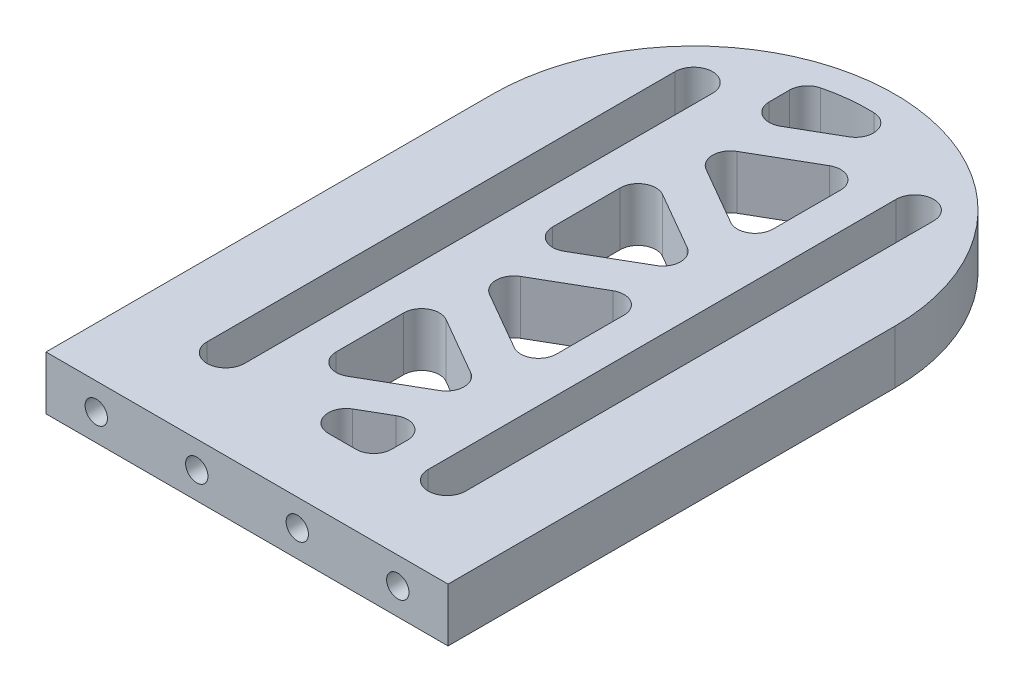
SolidWorks part; units mm, degrees
material "Сплав 2024"
ref_plane "Спереди" through (0, 0, 0) normal (0, 0, 1) x (1, 0, 0)
ref_plane "Сверху" through (0, 0, 0) normal (0, 1, 0) x (1, 0, 0)
ref_plane "Справа" through (0, 0, 0) normal (1, 0, 0) x (0, 0, -1)
sketch "Эскиз1" plane through (0, 0, 0) normal (0, 1, 0) x (1, 0, 0)
  line L2 (-15.9099, 15.9099) -> (15.9099, -15.9099) construction
  line L3 (15.9099, 15.9099) -> (-15.9099, -15.9099) construction
  line L4 (-22.5, 0) -> (-22.5, -50)
  line L5 (-22.5, -50) -> (22.5, -50)
  line L6 (22.5, 0) -> (22.5, -50)
  arc A0 (22.5, 0) -> (-22.5, 0) centre (0, 0) ccw
  dimension "D1" = 45
  dimension "D2" = 50
  dimension "D3" = 45
extrude "Бобышка-Вытянуть1" add sketch "Эскиз1" along normal blind 6
sketch "Эскиз2" plane through (0, 6, 0) normal (0, 1, 0) x (1, 0, 0)
  line L0 (-12.3744, -12.3744) -> (12.3744, 12.3744) construction
  line L1 (-36.6046, 36.6046) -> (36.6046, -36.6046) construction
  line L2 (22.5, -50) -> (22.5, 0) construction
  line L3 (-12.3744, 28.2466) -> (-12.3744, -50.5484) construction
  line L4 (12.3744, 23.4168) -> (12.3744, -56.6851) construction
  line L5 (-12.3744, 12.3744) -> (-12.3744, -40) construction
  line L6 (-10.2744, 12.3744) -> (-10.2744, -40)
  line L7 (-14.4744, 12.3744) -> (-14.4744, -40)
  line L8 (-22.5, -50) -> (22.5, -50) construction
  line L9 (0, 10.4779) -> (0, -10.8682) construction
  line L10 (12.3744, 12.3744) -> (12.3744, -40) construction
  line L11 (10.2744, 12.3744) -> (10.2744, -40)
  line L12 (14.4744, 12.3744) -> (14.4744, -40)
  circle A0 centre (0, 0) radius 6 construction
  circle A1 centre (0, 0) radius 17.5 construction
  arc A2 (-10.2744, 12.3744) -> (-14.4744, 12.3744) centre (-12.3744, 12.3744) ccw
  arc A3 (-14.4744, -40) -> (-10.2744, -40) centre (-12.3744, -40) ccw
  arc A4 (10.2744, 12.3744) -> (14.4744, 12.3744) centre (12.3744, 12.3744) cw
  arc A5 (14.4744, -40) -> (10.2744, -40) centre (12.3744, -40) cw
  point P12 (-12.3744, 12.3744)
  point P13 (12.3744, 12.3744)
  point P18 (-12.3744, -13.8128)
  point P28 (12.3744, -13.8128)
  dimension "D1" = 12
  dimension "D2" = 35
  dimension "D4" = 2.1
  dimension "D3" = 45
  dimension "D5" = 10
hole_wizard "Цековка для  винта с полукруглой головкой M31" [suppressed] positions "Эскиз4" profile "Эскиз5" counterbore size "M3" standard "Ansi Metric"
sketch "Эскиз4" plane through (0, 6, 0) normal (0, 1, 0) x (1, 0, 0)
  line L2 (-36.6046, 36.6046) -> (36.6046, -36.6046) construction
  line L3 (-12.3744, -12.3744) -> (12.3744, 12.3744) construction
  circle A0 centre (0, 0) radius 6 construction
  point P0 (-4.2426, 4.2426)
  point P6 (-4.2426, -4.2426)
  point P10 (4.2426, -4.2426)
  point P12 (4.2426, 4.2426)
sketch "Эскиз5" plane through (-4.2426, 6, -4.2426) normal (1, 0, 0) x (0, 0, 1)
  line L0 (0, 0) -> (0, 6)
  line L1 (0, 6) -> (1.7, 6)
  line L3 (1.7, 6) -> (1.7, 2)
  line L4 (1.7, 2) -> (3.35, 2)
  line L5 (3.35, 2) -> (3.35, 0)
  line L7 (3.35, 0) -> (0, 0)
  line L11 (0, -6.35) -> (0, 107.95) construction
  dimension "Диаметр сквозного отверстия" = 3.4
  dimension "Глубина сквозного отверстия" = 6
  dimension "Диаметр цековки" = 6.7
  dimension "Глубина цековки" = 2
hole_wizard "Отверстие обработанное метчиком M4x0.71" [suppressed] positions "Эскиз7" profile "Эскиз6" tap size "M4x0.7" standard "Ansi Metric"
sketch "Эскиз7" [suppressed] plane through (0, 4, 0) normal (0, 1, 0) x (1, 0, 0)
  line L0 (22.5, 0) -> (-22.5, 0) construction
  line L1 (0, 22.5) -> (0, -22.5) construction
  circle A0 centre (0, 0) radius 19.25 construction
  point P0 (-19.25, 0)
  point P6 (0, -19.25)
  point P10 (19.25, 0)
  point P12 (0, 19.25)
sketch "Эскиз6" plane through (-19.25, 4, 0) normal (1, 0, 0) x (0, 0, 1)
  line L0 (0, 0) -> (0, 4)
  line L1 (0, 4) -> (1.65, 4)
  line L2 (1.65, 4) -> (1.65, 0)
  line L5 (1.65, 0) -> (0, 0)
  line L11 (0, -6.35) -> (0, 107.95) construction
  dimension "Диаметр резьбы" = 3.3
  dimension "Глубина проходного сверла" = 4
extrude "Вырез-Вытянуть1" cut sketch "Эскиз2" against normal through all
sketch "Эскиз8" plane through (0, 0, 50) normal (0, 0, 1) x (1, 0, 0)
  line L0 (-22.5, 3) -> (22.5, 3) construction
  line L1 (-22.5, 6) -> (-22.5, 0) construction
  line L2 (22.5, 6) -> (22.5, 0) construction
  line L3 (-16.875, 6) -> (-16.875, 0) construction
  line L4 (-22.5, 6) -> (22.5, 6) construction
  line L5 (-22.5, 0) -> (22.5, 0) construction
  line L6 (-11.25, 6) -> (-11.25, 0) construction
  line L7 (-5.625, 6) -> (-5.625, 0) construction
  line L8 (0, 6) -> (0, 0) construction
  line L9 (-22.5, 0) -> (22.5, 0) construction
  line L10 (5.625, 0) -> (5.625, 6) construction
  line L11 (11.25, 6) -> (11.25, 0) construction
  line L12 (16.875, 6) -> (16.875, 0) construction
  dimension "D1" = 5.625
  dimension "D2" = 5.625
  dimension "D3" = 5.625
  dimension "D4" = 5.625
  dimension "D5" = 5.625
  dimension "D6" = 5.625
  dimension "D7" = 5.625
sketch "Эскиз11" plane through (0, 6, 0) normal (0, 1, 0) x (1, 0, 0)
  line L0 (-6.2744, -50) -> (-6.2744, 26.915) construction
  line L1 (-22.5, -50) -> (22.5, -50) construction
  line L2 (6.2744, -50) -> (6.2744, 26.915) construction
  line L3 (-10.2744, -40) -> (-10.2744, 12.3744) construction
  line L4 (6.2744, 18.5) -> (-6.2744, 11.255)
  line L5 (10.2744, 12.3744) -> (10.2744, -40) construction
  line L6 (-12.8062, 18.5) -> (12.8062, 18.5) construction
  line L7 (-6.2744, 11.255) -> (-6.2744, 18.5)
  line L8 (6.2744, 13.6272) -> (-6.2744, 6.3821)
  line L9 (-6.2744, 6.3821) -> (6.2744, -0.8629)
  line L10 (6.2744, -0.8629) -> (6.2744, 13.6272)
  line L11 (-6.2744, 1.5093) -> (6.2744, -5.7357)
  line L12 (6.2744, -5.7357) -> (-6.2744, -12.9807)
  line L13 (-6.2744, -12.9807) -> (-6.2744, 1.5093)
  line L14 (-6.2744, -17.8536) -> (6.2744, -10.6085)
  line L15 (6.2744, -10.6085) -> (6.2744, -25.0986)
  line L16 (6.2744, -25.0986) -> (-6.2744, -17.8536)
  line L17 (-6.2744, -22.7264) -> (6.2744, -29.9714)
  line L18 (6.2744, -29.9714) -> (-6.2744, -37.2164)
  line L19 (-6.2744, -37.2164) -> (-6.2744, -22.7264)
  line L20 (-6.2744, -42.0893) -> (6.2744, -34.8442)
  line L21 (6.2744, -34.8442) -> (6.2744, -42.0893)
  line L22 (6.2744, -42.0893) -> (-6.2744, -42.0893)
  line L23 (22.5, -42.1) -> (-22.5, -42.1) construction
  line L24 (22.5, 0) -> (22.5, -50) construction
  line L25 (-22.5, 0) -> (-22.5, -50) construction
  arc A0 (22.5, 0) -> (-22.5, 0) centre (0, 0) ccw construction
  arc A1 (-14.4744, -40) -> (-10.2744, -40) centre (-12.3744, -40) ccw construction
  arc A2 (-6.2744, 18.5) -> (6.2744, 18.5) centre (0, 0) cw
  point P16 (0, 22.5)
  point P17 (-6.2744, 18.5)
  point P18 (6.2744, 18.5)
  dimension "D3" = 4
  dimension "D4" = 30
  dimension "D1" = 4
  dimension "D2" = 4
  dimension "D5" = 60
  dimension "D6" = 60
  dimension "D7" = 60
  dimension "D8" = 60
  dimension "D9" = 4.22
  dimension "D10" = 4.22
  dimension "D11" = 4.22
  dimension "D12" = 4.22
  dimension "D13" = 4.22
extrude "Вырез-Вытянуть2" cut sketch "Эскиз11" against normal up to next
fillet "Скругление18" radius 2 18 edges at (6.2744, 3, 25.0986) (6.2744, 3, 0.8629) (-6.2744, 3, -18.5) (-6.2744, 3, -1.5093) (-6.2744, 3, 22.7264) (-6.2744, 3, -6.3821) (-6.2744, 3, 17.8536) (-6.2744, 3, -11.255) (-6.2744, 3, 12.9807) (-6.2744, 3, 37.2164) (6.2744, 3, -18.5) (6.2744, 3, 5.7357) (6.2744, 3, 29.9714) (6.2744, 3, -13.6272) (6.2744, 3, 10.6085) (6.2744, 3, 34.8442) (6.2744, 3, 42.0893) (-6.2744, 3, 42.0893)
hole_wizard "Отверстие обработанное метчиком M3x0.51" positions "Эскиз10" profile "Эскиз9" tap size "M3x0.5" standard "Ansi Metric"
sketch "Эскиз10" plane through (0, 0, 50) normal (0, 0, 1) x (1, 0, 0)
  line L0 (-16.875, 6) -> (-16.875, 0) construction
  line L4 (16.875, 6) -> (16.875, 0) construction
  line L6 (5.625, 0) -> (5.625, 6) construction
  line L8 (-5.625, 6) -> (-5.625, 0) construction
  point P0 (-16.875, 3)
  point P4 (-5.625, 3)
  point P8 (5.625, 3)
  point P12 (16.875, 3)
sketch "Эскиз9" plane through (-16.875, 3, 50) normal (1, 0, 0) x (0, -1, 0)
  line L0 (0, 0) -> (0, 9.2511)
  line L1 (0, 9.2511) -> (1.25, 8.5)
  line L2 (1.25, 8.5) -> (1.25, 0)
  line L5 (1.25, 0) -> (0, 0)
  line L10 (0, 9.2511) -> (-1.25, 8.5) construction
  line L11 (0, -6.35) -> (0, 107.95) construction
  dimension "Диаметр сверла" = 2.5
  dimension "Глубина сверла" = 8.5
  dimension "Угол заточки сверла" = 118
cosmetic thread "Отверстие резьбы1" parameters "D1"=6, "D2"=3
cosmetic thread "Отверстие резьбы2" parameters "D1"=6, "D2"=3
cosmetic thread "Отверстие резьбы3" parameters "D1"=6, "D2"=3
cosmetic thread "Отверстие резьбы4" parameters "D1"=6, "D2"=3
equation "\"D1@Эскиз8\"=\"D1@Эскиз1\"/8"
equation "\"D2@Эскиз8\"=\"D1@Эскиз8\""
equation "\"D3@Эскиз8\"=\"D1@Эскиз8\""
equation "\"D4@Эскиз8\"=\"D1@Эскиз8\""
equation "\"D10@Эскиз11\"=\"D9@Эскиз11\""
equation "\"D11@Эскиз11\"=\"D9@Эскиз11\""
equation "\"D12@Эскиз11\"=\"D9@Эскиз11\""
equation "\"D13@Эскиз11\"=\"D9@Эскиз11\""
equation "\"D5@Эскиз8\"=\"D1@Эскиз8\""
equation "\"D6@Эскиз8\"=\"D1@Эскиз8\""
equation "\"D7@Эскиз8\"=\"D1@Эскиз8\""
